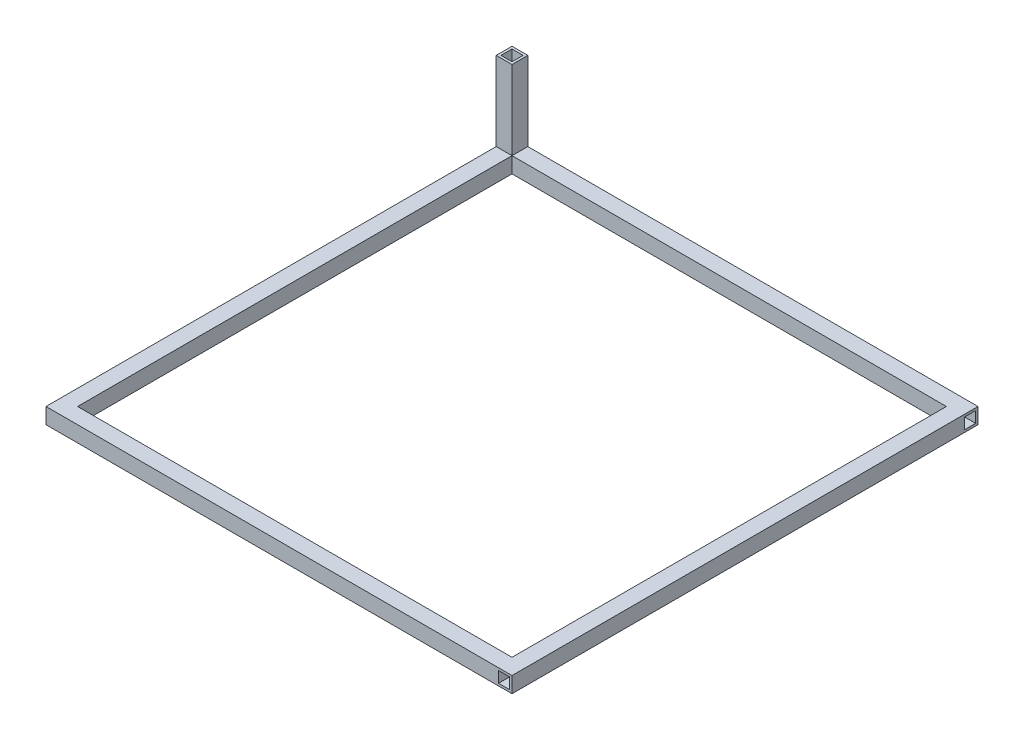
SolidWorks part; units mm, degrees
ref_plane "前视基准面" through (0, 0, 0) normal (0, 0, 1) x (1, 0, 0)
ref_plane "上视基准面" through (0, 0, 0) normal (0, 1, 0) x (1, 0, 0)
ref_plane "右视基准面" through (0, 0, 0) normal (1, 0, 0) x (0, 0, -1)
other "Configuration Table"
sketch "草图1" plane through (0, 0, 0) normal (0, 0, 1) x (1, 0, 0)
  line L1 (-69.505, 30.9956) -> (-49.505, 30.9956)
  line L2 (-69.505, 30.9956) -> (-69.505, 10.9956)
  line L3 (-69.505, 10.9956) -> (-49.505, 10.9956)
  line L4 (-49.505, 30.9956) -> (-49.505, 10.9956)
  line L5 (-66.505, 27.9956) -> (-52.505, 27.9956)
  line L6 (-66.505, 27.9956) -> (-66.505, 13.9956)
  line L7 (-66.505, 13.9956) -> (-52.505, 13.9956)
  line L8 (-52.505, 27.9956) -> (-52.505, 13.9956)
  dimension "D1" = 20
  dimension "D2" = 20
  dimension "D3" = 3
  dimension "D4" = 14
  dimension "D5" = 14
  dimension "D6" = 3
extrude "凸台-拉伸1" add sketch "草图1" along normal blind 570
sketch "草图2" plane through (0, 30.9956, 0) normal (0, 1, 0) x (1, 0, 0)
  line L0 (-49.505, -570) -> (-49.505, 0) construction
  line L1 (-69.505, 0) -> (-49.505, 0)
  line L2 (-69.505, 0) -> (-69.505, -20)
  line L3 (-69.505, -20) -> (-49.505, -20)
  line L4 (-49.505, 0) -> (-49.505, -20)
  line L6 (-66.505, -3) -> (-52.505, -3)
  line L7 (-66.505, -3) -> (-66.505, -17)
  line L8 (-66.505, -17) -> (-52.505, -17)
  line L9 (-52.505, -3) -> (-52.505, -17)
  dimension "D1" = 20
  dimension "D2" = 14
  dimension "D3" = 14
  dimension "D4" = 3
  dimension "D5" = 3
extrude "凸台-拉伸2" add sketch "草图2" along normal blind 100
sketch "草图5" plane through (-49.505, 0, 0) normal (1, 0, 0) x (0, 0, -1)
  line L1 (-20, 30.9956) -> (0, 30.9956)
  line L2 (-20, 30.9956) -> (-20, 10.9956)
  line L3 (-20, 10.9956) -> (0, 10.9956)
  line L4 (0, 30.9956) -> (0, 10.9956)
  line L5 (-17, 27.9956) -> (-3, 27.9956)
  line L6 (-17, 27.9956) -> (-17, 13.9956)
  line L7 (-17, 13.9956) -> (-3, 13.9956)
  line L8 (-3, 27.9956) -> (-3, 13.9956)
  dimension "D1" = 14
  dimension "D2" = 14
  dimension "D3" = 3
  dimension "D4" = 3
extrude "凸台-拉伸3" add sketch "草图5" along normal blind 570
sketch "草图6" plane through (0, 0, 20) normal (0, 0, 1) x (1, 0, 0)
  line L0 (520.495, 10.9956) -> (-49.505, 10.9956) construction
  line L1 (520.495, 30.9956) -> (500.495, 30.9956)
  line L2 (520.495, 30.9956) -> (520.495, 10.9956)
  line L3 (520.495, 10.9956) -> (500.495, 10.9956)
  line L4 (500.495, 30.9956) -> (500.495, 10.9956)
  line L6 (503.495, 27.9956) -> (517.495, 27.9956)
  line L7 (503.495, 27.9956) -> (503.495, 13.9956)
  line L8 (503.495, 13.9956) -> (517.495, 13.9956)
  line L9 (517.495, 27.9956) -> (517.495, 13.9956)
  dimension "D1" = 20
  dimension "D2" = 14
  dimension "D3" = 14
  dimension "D4" = 3
  dimension "D5" = 3
extrude "凸台-拉伸4" add sketch "草图6" along normal blind 570
sketch "草图7" plane through (500.495, 0, 0) normal (-1, 0, 0) x (0, 0, 1)
  line L1 (570, 30.9956) -> (590, 30.9956)
  line L2 (570, 30.9956) -> (570, 10.9956)
  line L3 (570, 10.9956) -> (590, 10.9956)
  line L4 (590, 30.9956) -> (590, 10.9956)
  line L5 (573, 27.9956) -> (587, 27.9956)
  line L6 (573, 27.9956) -> (573, 13.9956)
  line L7 (573, 13.9956) -> (587, 13.9956)
  line L8 (587, 27.9956) -> (587, 13.9956)
  dimension "D1" = 3
  dimension "D2" = 3
  dimension "D3" = 14
  dimension "D4" = 14
extrude "凸台-拉伸5" add sketch "草图7" along normal blind 570
